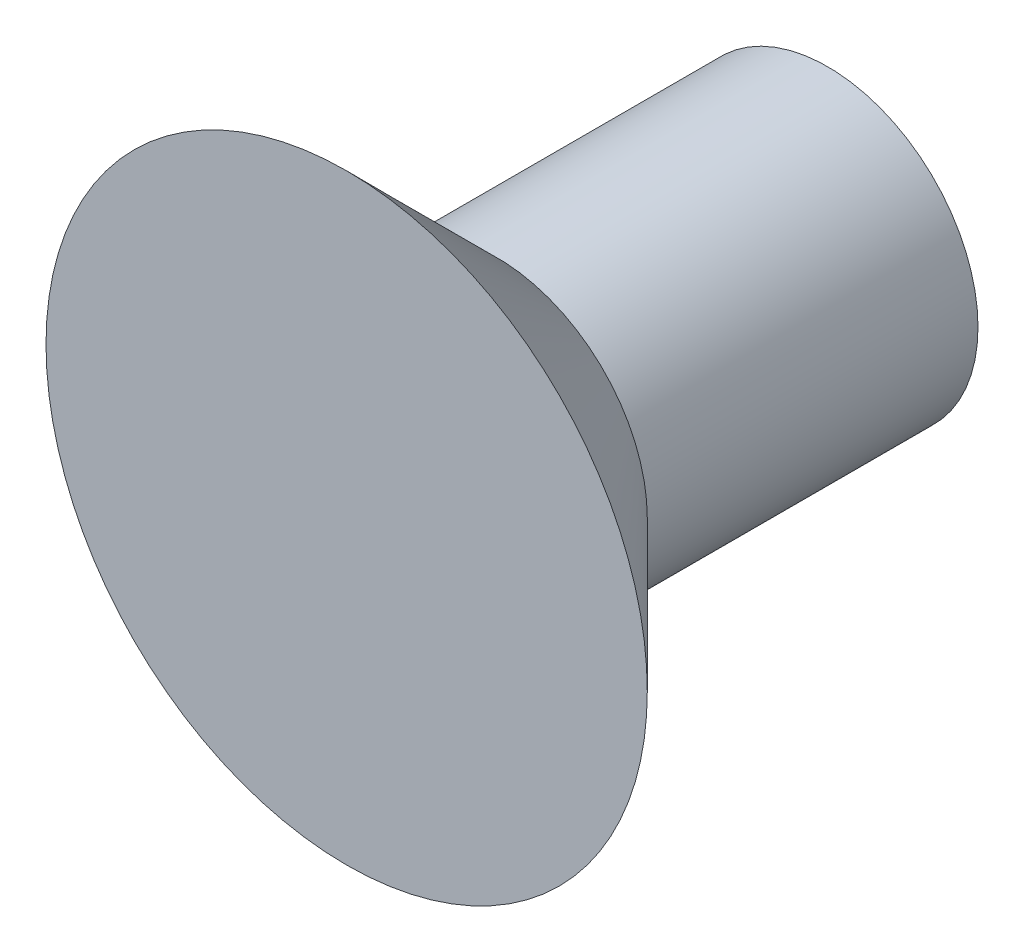
SolidWorks part; units mm, degrees
material "AISI 4340 Steel, normalized"
ref_plane "Front Plane" through (0, 0, 0) normal (0, 0, 1) x (1, 0, 0)
ref_plane "Top Plane" through (0, 0, 0) normal (0, 1, 0) x (1, 0, 0)
ref_plane "Right Plane" through (0, 0, 0) normal (1, 0, 0) x (0, 0, -1)
sketch "Sketch1" plane through (0, 0, 0) normal (0, 0, 1) x (1, 0, 0)
  circle A0 centre (0, 0) radius 2.5
extrude "Countersunk_Head_D5" add sketch "Sketch1" against normal blind 1.25 draft 45
sketch "Sketch2" plane through (0, 0, 0) normal (0, 0, 1) x (1, 0, 0)
  circle A0 centre (0, 0) radius 1.25
extrude "M2p5_Thread_Envelope" add sketch "Sketch2" along normal blind 2.75 from offset 4
